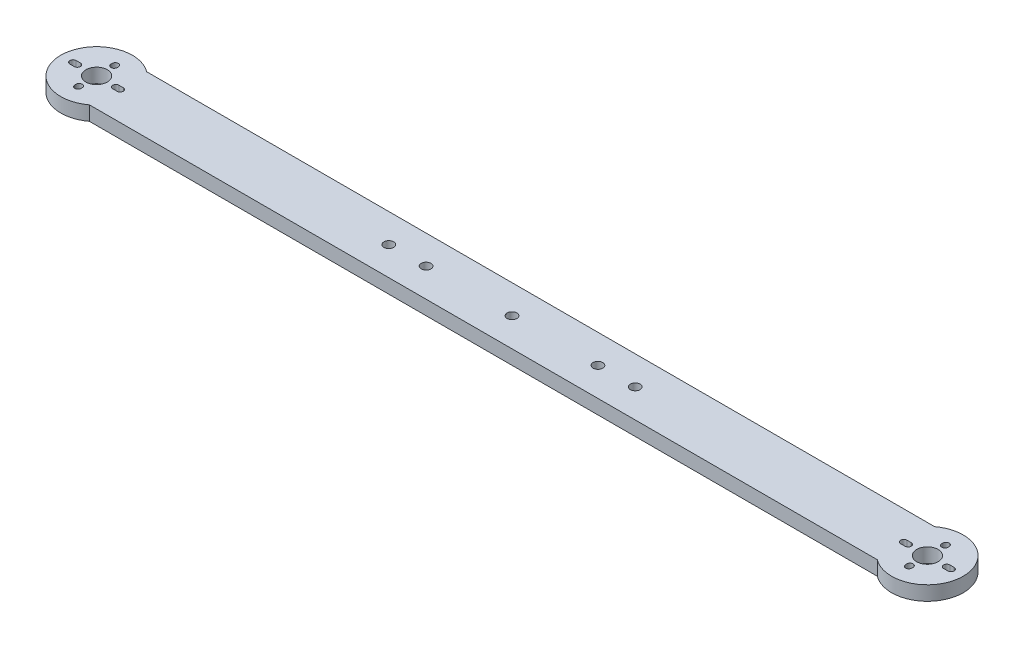
SolidWorks part; units mm, degrees
material "Thornel Mat VMA"
ref_plane "Front Plane" through (0, 0, 0) normal (0, 0, 1) x (1, 0, 0)
ref_plane "Top Plane" through (0, 0, 0) normal (0, 1, 0) x (1, 0, 0)
ref_plane "Right Plane" through (0, 0, 0) normal (1, 0, 0) x (0, 0, -1)
sketch "Sketch1" plane through (0, 0, 0) normal (0, 1, 0) x (1, 0, 0)
  line L0 (0, 12.7) -> (0, -12.7) construction
  line L1 (-174.625, 12.7) -> (174.625, 12.7)
  line L3 (-174.625, -12.7) -> (174.625, -12.7)
  arc A0 (-174.625, 12.7) -> (-174.625, -12.7) centre (-184.15, 0) ccw
  arc A1 (174.625, -12.7) -> (174.625, 12.7) centre (184.15, 0) ccw
  point P8 (0, 12.7)
  point P12 (0, 0)
  dimension "D3" = 31.75
  dimension "D4" = 31.75
extrude "Boss-Extrude1" add sketch "Sketch1" along normal blind 6.35
sketch "Sketch2" plane through (0, 6.35, 0) normal (0, 1, 0) x (1, 0, 0)
  line L0 (173.6914, 0) -> (175.6086, 0) construction
  line L1 (173.6914, 1.375) -> (175.6086, 1.375)
  line L2 (173.6914, -1.375) -> (175.6086, -1.375)
  line L3 (184.15, 0) -> (184.15, 3.2374) construction
  line L4 (194.6086, 0) -> (192.6914, 0) construction
  line L5 (194.6086, 1.375) -> (192.6914, 1.375)
  line L6 (194.6086, -1.375) -> (192.6914, -1.375)
  line L7 (184.15, 8.25) -> (184.15, 7.75) construction
  line L8 (185.525, 8.25) -> (185.525, 7.75)
  line L9 (182.775, 8.25) -> (182.775, 7.75)
  line L10 (184.15, -8.25) -> (184.15, -7.75) construction
  line L11 (185.525, -8.25) -> (185.525, -7.75)
  line L12 (182.775, -8.25) -> (182.775, -7.75)
  line L13 (0, 0) -> (184.15, 0) construction
  line L14 (0, 0) -> (0, 12.7) construction
  line L15 (174.625, 12.7) -> (-174.625, 12.7) construction
  line L16 (-184.15, 0) -> (-184.15, 3.2374) construction
  line L17 (-184.15, -8.25) -> (-184.15, -7.75) construction
  line L18 (-185.525, -8.25) -> (-185.525, -7.75)
  line L19 (-182.775, -8.25) -> (-182.775, -7.75)
  line L20 (-184.15, 8.25) -> (-184.15, 7.75) construction
  line L21 (-185.525, 8.25) -> (-185.525, 7.75)
  line L22 (-182.775, 8.25) -> (-182.775, 7.75)
  line L23 (-194.6086, 0) -> (-192.6914, 0) construction
  line L24 (-194.6086, 1.375) -> (-192.6914, 1.375)
  line L25 (-194.6086, -1.375) -> (-192.6914, -1.375)
  line L26 (-173.6914, 0) -> (-175.6086, 0) construction
  line L27 (-173.6914, 1.375) -> (-175.6086, 1.375)
  line L28 (-173.6914, -1.375) -> (-175.6086, -1.375)
  line L29 (184.15, -8) -> (184.15, 8) construction
  circle A0 centre (184.15, 0) radius 4.75
  arc A1 (173.6914, 1.375) -> (173.6914, -1.375) centre (173.6914, 0) ccw
  arc A2 (175.6086, -1.375) -> (175.6086, 1.375) centre (175.6086, 0) ccw
  arc A3 (194.6086, 1.375) -> (194.6086, -1.375) centre (194.6086, 0) cw
  arc A4 (192.6914, -1.375) -> (192.6914, 1.375) centre (192.6914, 0) cw
  arc A5 (185.525, 8.25) -> (182.775, 8.25) centre (184.15, 8.25) ccw
  arc A6 (182.775, 7.75) -> (185.525, 7.75) centre (184.15, 7.75) ccw
  arc A7 (185.525, -8.25) -> (182.775, -8.25) centre (184.15, -8.25) cw
  arc A8 (182.775, -7.75) -> (185.525, -7.75) centre (184.15, -7.75) cw
  circle A9 centre (-184.15, 0) radius 4.75
  arc A10 (-185.525, -8.25) -> (-182.775, -8.25) centre (-184.15, -8.25) ccw
  arc A11 (-182.775, -7.75) -> (-185.525, -7.75) centre (-184.15, -7.75) ccw
  arc A12 (-185.525, 8.25) -> (-182.775, 8.25) centre (-184.15, 8.25) cw
  arc A13 (-182.775, 7.75) -> (-185.525, 7.75) centre (-184.15, 7.75) cw
  arc A14 (-194.6086, 1.375) -> (-194.6086, -1.375) centre (-194.6086, 0) ccw
  arc A15 (-192.6914, -1.375) -> (-192.6914, 1.375) centre (-192.6914, 0) ccw
  arc A16 (-173.6914, 1.375) -> (-173.6914, -1.375) centre (-173.6914, 0) cw
  arc A17 (-175.6086, -1.375) -> (-175.6086, 1.375) centre (-175.6086, 0) cw
  point P4 (174.65, 0)
  point P12 (193.65, 0)
  point P19 (184.15, 8)
  point P26 (184.15, -8)
  point P41 (-184.15, -8)
  point P48 (-184.15, 8)
  point P55 (-193.65, 0)
  point P62 (-174.65, 0)
  point P69 (184.15, 0)
  dimension "D4" = 9.5
  dimension "D1" = 16
  dimension "D2" = 19
  dimension "D3" = 184.15
  dimension "D5" = 0.5
extrude "Cut-Extrude1" cut sketch "Sketch2" against normal through all
sketch "Sketch3" plane through (0, 6.35, 0) normal (0, 1, 0) x (1, 0, 0)
  circle A0 centre (0, 0) radius 2.159
  circle A1 centre (38.1, 0) radius 2.159
  circle A2 centre (-38.1, 0) radius 2.159
  dimension "D1" = 38.1
  dimension "D3" = 4.318
  dimension "D4" = 4.318
  dimension "D5" = 4.318
  dimension "D2" = 38.1
extrude "Cut-Extrude2" cut sketch "Sketch3" against normal through all
sketch "Sketch4" plane through (0, 6.35, 0) normal (0, 1, 0) x (1, 0, 0)
  line L0 (0, 12.7) -> (0, -33.8789) construction
  line L1 (174.625, 12.7) -> (-174.625, 12.7) construction
  circle A0 centre (54.61, 0) radius 2.159
  circle A1 centre (184.15, 0) radius 4.75 construction
  circle A2 centre (-54.61, 0) radius 2.159
  dimension "D1" = 4.318
  dimension "D2" = 129.54
extrude "Cut-Extrude3" cut sketch "Sketch4" against normal through all
